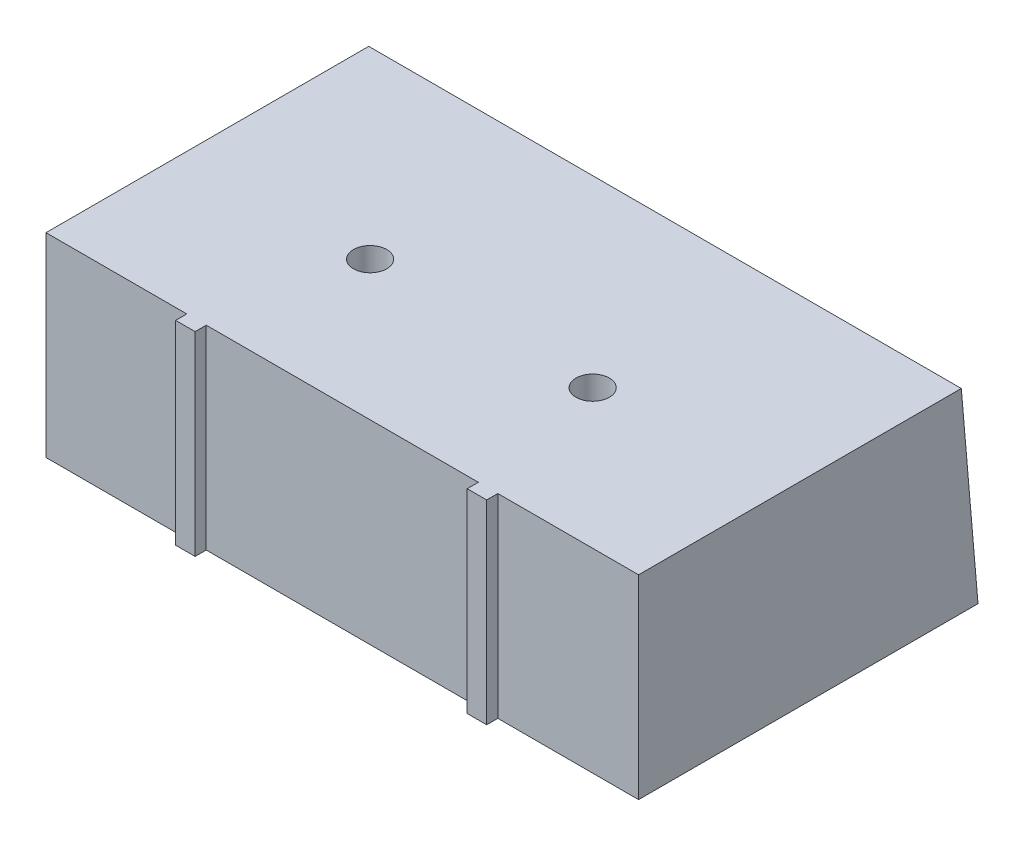
SolidWorks part; units mm, degrees
ref_plane "Front Plane" through (0, 0, 0) normal (0, 0, 1) x (1, 0, 0)
ref_plane "Top Plane" through (0, 0, 0) normal (0, 1, 0) x (1, 0, 0)
ref_plane "Right Plane" through (0, 0, 0) normal (1, 0, 0) x (0, 0, -1)
sketch "Sketch1" plane through (0, 0, 0) normal (0, 1, 0) x (1, 0, 0)
  line L0 (33.25, 25) -> (73.25, 25) construction
  line L1 (0, 0) -> (25.3, 0)
  line L2 (0, 0) -> (0, 61)
  line L3 (0, 61) -> (106.5, 61)
  line L4 (106.5, 0) -> (106.5, 61)
  line L5 (25.3, 0) -> (25.3, -2)
  line L6 (25.3, -2) -> (28.8, -2)
  line L7 (28.8, -2) -> (28.8, 0)
  line L8 (53.25, 61) -> (53.25, 0) construction
  line L9 (77.7, -2) -> (77.7, 0)
  line L10 (81.2, -2) -> (77.7, -2)
  line L11 (0.75, 0) -> (25.3, 0) construction
  line L12 (81.2, 0) -> (81.2, -2)
  line L13 (0.75, 0) -> (0.75, 31.2581) construction
  line L14 (28.8, 0) -> (77.7, 0) construction
  line L15 (28.8, 0) -> (77.7, 0)
  line L16 (81.2, 0) -> (105.75, 0) construction
  line L17 (81.2, 0) -> (106.5, 0)
  line L18 (0.75, 31.2581) -> (35.75, 31.2581) construction
  line L19 (35.75, 31.2581) -> (35.75, 20.0951) construction
  circle A0 centre (33.25, 25) radius 3
  circle A1 centre (73.25, 25) radius 3
  point P19 (27.05, -2)
  point P22 (53.25, 25)
  dimension "D9" = 6
  dimension "D10" = 0.75
  dimension "D1" = 40
  dimension "D2" = 106.5
  dimension "D3" = 61
  dimension "D4" = 105
  dimension "D5" = 26.3
  dimension "D6" = 2
  dimension "D7" = 3.5
  dimension "D8" = 25
  dimension "D11" = 35
extrude "Boss-Extrude2" add sketch "Sketch1" along normal blind 35
sketch "Sketch2" plane through (0, 0, 0) normal (-1, 0, 0) x (0, 0, 1)
  line L0 (-61, 35) -> (-58, 35)
  line L1 (-61, 35) -> (0, 35) construction
  line L2 (-58, 35) -> (-61, 0)
  line L3 (-61, 35) -> (-61, 0)
  dimension "D1" = 3
extrude "Cut-Extrude1" cut sketch "Sketch2" against normal through all both and the other way through all
